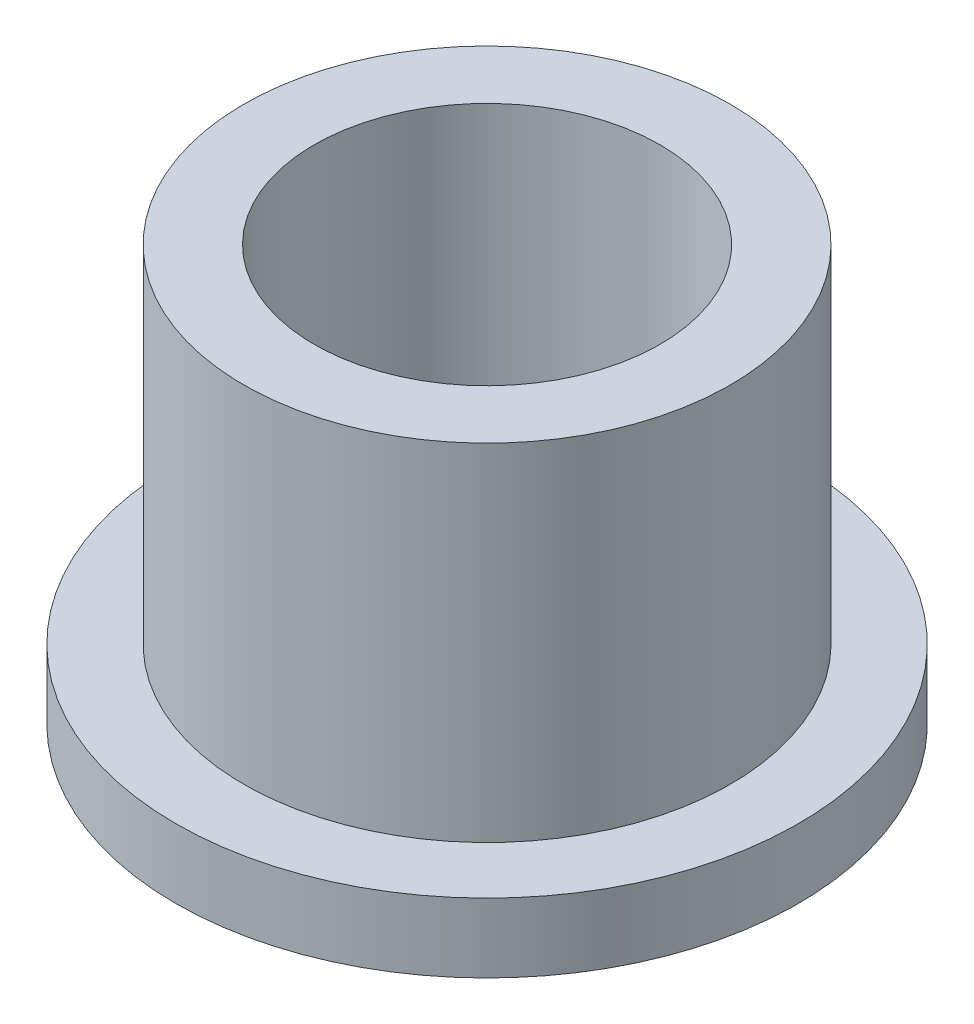
SolidWorks part; units mm, degrees
ref_plane "Front" through (0, 0, 0) normal (0, 0, 1) x (1, 0, 0)
ref_plane "Top" through (0, 0, 0) normal (0, 1, 0) x (1, 0, 0)
ref_plane "Right" through (0, 0, 0) normal (1, 0, 0) x (0, 0, -1)
sketch "Sketch1" plane through (0, 0, 0) normal (0, 1, 0) x (1, 0, 0)
  circle A0 centre (0, 0) radius 3.9688
  circle A1 centre (0, 0) radius 5.5816
  circle A2 centre (0, 0) radius 7.1438
  dimension "ID" = 7.9375
  dimension "OD" = 11.1633
  dimension "FlangeOD" = 14.2875
sketch "Sketch2" plane through (0, 0, 0) normal (0, 1, 0) x (1, 0, 0)
  circle A0 centre (0, 0) radius 3.9688 construction
  circle A1 centre (0, 0) radius 5.5817 construction
  circle A2 centre (0, 0) radius 3.9688
  circle A3 centre (0, 0) radius 5.5817
extrude "Boss-Extrude1" add sketch "Sketch2" along normal blind 9.525
sketch "Sketch3" plane through (0, 0, 0) normal (0, 1, 0) x (1, 0, 0)
  circle A0 centre (0, 0) radius 7.1438 construction
  circle A1 centre (0, 0) radius 5.5817 construction
  circle A2 centre (0, 0) radius 7.1438
  circle A3 centre (0, 0) radius 5.5817
extrude "Boss-Extrude2" add sketch "Sketch3" along normal blind 1.5875
